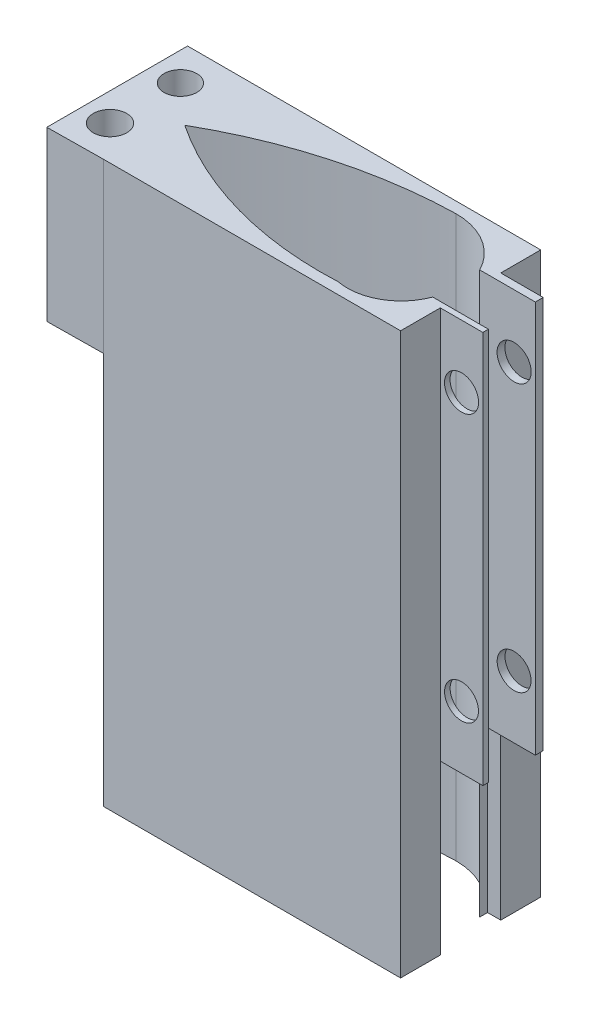
SolidWorks part; units mm, degrees
ref_plane "Front Plane" through (0, 0, 0) normal (0, 0, 1) x (1, 0, 0)
ref_plane "Top Plane" through (0, 0, 0) normal (0, 1, 0) x (1, 0, 0)
ref_plane "Right Plane" through (0, 0, 0) normal (1, 0, 0) x (0, 0, -1)
sketch "Sketch1" plane through (0, 0, 0) normal (0, 1, 0) x (1, 0, 0)
  line L1 (0, 0) -> (67.3209, 0)
  line L2 (0, 0) -> (0, -31.7448)
  line L3 (0, -31.7448) -> (67.3209, -31.7448)
  line L4 (67.3209, 0) -> (67.3209, -31.7448)
extrude "Boss-Extrude1" add sketch "Sketch1" along normal blind 127 contours L2 L1 L4 L3
sketch "Sketch2" plane through (0, 127, 0) normal (0, 1, 0) x (1, 0, 0)
  line L0 (0, 0) -> (-12.6918, 0)
  line L1 (-12.6918, 0) -> (-12.6918, -31.893)
  line L2 (-12.6918, -31.893) -> (0, -31.7448)
  line L3 (0, -31.7448) -> (0, 0)
extrude "Boss-Extrude2" add sketch "Sketch2" against normal blind 38.1 contours L3 L0 L1 L2
sketch "Sketch3" plane through (0, 127, 0) normal (0, 1, 0) x (1, 0, 0)
  line L0 (-12.6918, -15.9465) -> (0, -15.9465)
  line L1 (-12.6918, 0) -> (-12.6918, -31.893) construction
  circle A0 centre (-6.3459, -23.9198) radius 3.7987
extrude "Cut-Extrude1" cut sketch "Sketch3" against normal blind 53.34 contours A0
sketch "Sketch4" plane through (0, 127, 0) normal (0, 1, 0) x (1, 0, 0)
  line L8 (-17.7261, 1.0229) -> (-17.6101, 1.0229)
  circle A0 centre (-6.2389, -8.0749) radius 3.713
extrude "Cut-Extrude2" cut sketch "Sketch4" against normal blind 72.898 contours A0
sketch "Sketch5" plane through (0, 127, 0) normal (0, 1, 0) x (1, 0, 0)
  line L0 (0, 0) -> (0, -31.7448)
  line L1 (67.3209, -15.8724) -> (67.3209, -12.0147)
  line L2 (67.3209, 0) -> (67.3209, -31.7448) construction
  line L3 (67.3209, -12.0147) -> (73.78, -12.0147)
  line L4 (73.78, -12.0147) -> (73.78, -19.5366)
  line L5 (73.78, -19.5366) -> (67.3209, -19.5366)
  line L6 (67.3209, -19.5366) -> (67.3209, -15.8724)
  line L7 (0, 0) -> (50.6455, 0)
  line L8 (-12.6918, 0) -> (67.3209, 0) construction
  line L10 (0, -31.7448) -> (67.3209, -31.7448) construction
  line L13 (67.3209, -12.0147) -> (64.8844, -12.0147)
  line L14 (67.3209, -19.5366) -> (64.8844, -19.5366)
  arc A0 (0, -15.8724) -> (50.6455, 0) centre (52.5014, -94.6574) cw
  arc A1 (50.6455, 0) -> (67.3209, -12.0147) centre (50.4446, -17.8583) cw
  arc A2 (50.6455, -31.7448) -> (67.3209, -19.5366) centre (52.8791, -17.303) ccw
  arc A3 (0, -15.8724) -> (50.6455, -31.7448) centre (47.9417, 48.3637) ccw
  arc A4 (2.546, -15.8724) -> (50.6455, -2.4899) centre (52.8779, -103.6444) cw
  arc A5 (2.546, -15.8724) -> (50.6455, -29.1917) centre (46.6879, 50.0262) ccw
  arc A6 (50.6455, -29.1917) -> (64.8844, -19.5366) centre (52.9374, -17.2447) ccw
  arc A7 (50.6455, -2.4899) -> (64.8844, -12.0147) centre (50.6631, -17.8691) cw
  arc A8 (64.8844, -12.0147) -> (64.8844, -19.5366) centre (49.5065, -15.7757) cw
extrude "Cut-Extrude3" cut sketch "Sketch5" against normal blind 177.8 contours A8 A7 A4 A5 A6
sketch "Sketch6" plane through (0, 127, 0) normal (0, 1, 0) x (1, 0, 0)
  line L1 (67.3209, 0) -> (67.3209, -31.7448) construction
  line L2 (64.3382, -15.8724) -> (64.3382, -22.7479)
  line L3 (64.3382, -22.7479) -> (67.3209, -22.7479)
  line L4 (67.3209, -22.7479) -> (67.3209, -9.0547)
  line L5 (67.3209, -9.0547) -> (64.3382, -9.0547)
  line L6 (64.3382, -9.0547) -> (64.3382, -15.8724)
extrude "Cut-Extrude4" cut sketch "Sketch6" against normal blind 140.7527 contours L2 L3 L4 L5 L6
sketch "Sketch7" plane through (0, 127, 0) normal (0, 1, 0) x (1, 0, 0)
  line L0 (64.3382, -9.0547) -> (64.3382, -10.8326)
  line L1 (64.3382, -10.8326) -> (76.9364, -10.8326)
  line L2 (76.9364, -10.8326) -> (76.9364, -9.0547)
  line L3 (76.9364, -9.0547) -> (64.3382, -9.0547)
extrude "Boss-Extrude3" add sketch "Sketch7" against normal blind 88.9367
sketch "Sketch8" plane through (0, 127, 0) normal (0, 1, 0) x (1, 0, 0)
  line L0 (64.3382, -22.7479) -> (64.3382, -21.4881)
  line L1 (64.3382, -21.4881) -> (76.96, -21.4881)
  line L2 (76.96, -21.4881) -> (76.96, -22.7479)
  line L3 (76.96, -22.7479) -> (64.3382, -22.7479)
extrude "Boss-Extrude4" add sketch "Sketch8" against normal blind 88.9367
sketch "Sketch9" plane through (0, 0, 9.0547) normal (0, 0, -1) x (-1, 0, 0)
  circle A0 centre (-72.1287, 112.8052) radius 3.8624
extrude "Cut-Extrude5" cut sketch "Sketch9" against normal blind 31.2787
sketch "Sketch10" plane through (0, 0, 9.0547) normal (0, 0, -1) x (-1, 0, 0)
  line L0 (-72.1287, 112.8052) -> (-72.1287, 127)
  line L1 (-76.9364, 127) -> (-67.3209, 127) construction
  circle A0 centre (-72.1287, 52.199) radius 3.842
extrude "Cut-Extrude6" cut sketch "Sketch10" against normal blind 32.5487 contours A0
